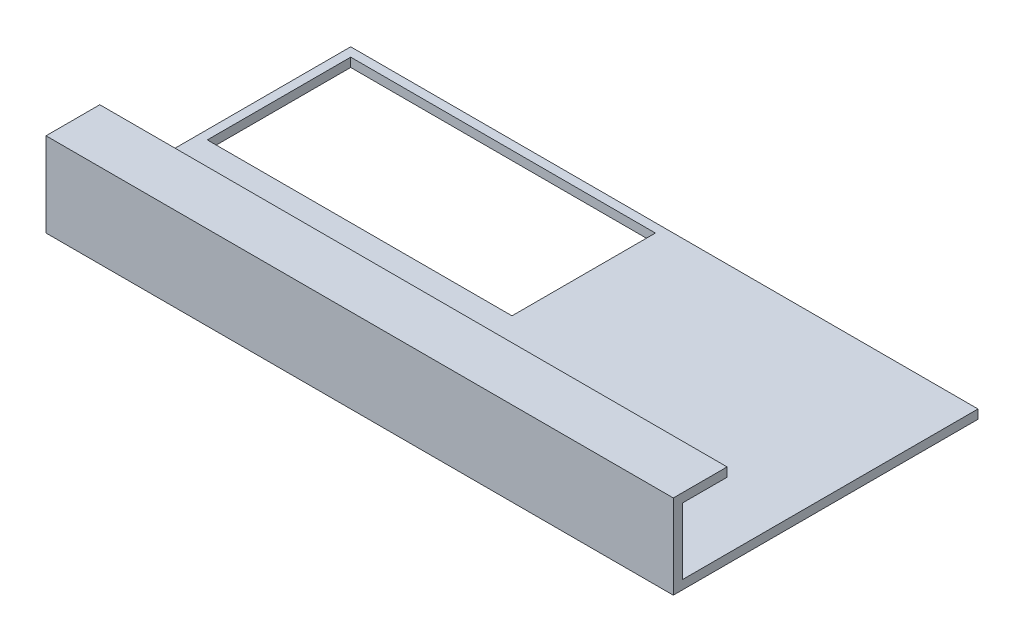
SolidWorks part; units mm, degrees
ref_plane "Front Plane" through (0, 0, 0) normal (0, 0, 1) x (1, 0, 0)
ref_plane "Top Plane" through (0, 0, 0) normal (0, 1, 0) x (1, 0, 0)
ref_plane "Right Plane" through (0, 0, 0) normal (1, 0, 0) x (0, 0, -1)
sketch "Sketch1" plane through (0, 0, 0) normal (0, 1, 0) x (1, 0, 0)
  line L1 (-87.5, -42.5) -> (87.5, -42.5)
  line L2 (-87.5, -42.5) -> (-87.5, 42.5)
  line L3 (-87.5, 42.5) -> (87.5, 42.5)
  line L4 (87.5, -42.5) -> (87.5, 42.5)
  line L5 (-87.5, -42.5) -> (87.5, 42.5) construction
  line L6 (-87.5, 42.5) -> (87.5, -42.5) construction
  point P0 (0, 0)
  dimension "D1" = 175
  dimension "D2" = 85
extrude "Boss-Extrude1" add sketch "Sketch1" along normal blind 2.5
sketch "Sketch2" plane through (0, 0, 0) normal (0, -1, 0) x (1, 0, 0)
  line L0 (-85, 0) -> (-85, -40)
  line L3 (-85, 0) -> (0, 0)
  line L4 (0, -40) -> (0, 0)
  line L5 (0, -40) -> (-85, -40)
  dimension "D1" = 85
  dimension "D2" = 40
extrude "Cut-Extrude1" cut sketch "Sketch2" against normal up to surface (2.5 mm away) up to face at (0, 2.5, 0)
sketch "Sketch3" plane through (0, 2.5, 0) normal (0, 1, 0) x (1, 0, 0)
  line L0 (87.5, -42.5) -> (87.5, 42.5) construction
  line L1 (-87.5, -42.5) -> (87.5, -42.5)
  line L2 (-87.5, -42.5) -> (-87.5, -40)
  line L3 (-87.5, -40) -> (87.5, -40)
  line L4 (87.5, -42.5) -> (87.5, -40)
  dimension "D1" = 2.5
extrude "Boss-Extrude2" add sketch "Sketch3" along normal blind 18.5
sketch "Sketch4" plane through (0, 21, 0) normal (0, 1, 0) x (1, 0, 0)
  line L0 (87.5, -40) -> (87.5, 42.5) construction
  line L1 (-87.5, -42.5) -> (87.5, -42.5)
  line L2 (-87.5, -42.5) -> (-87.5, -27.495)
  line L3 (-87.5, -27.495) -> (87.5, -27.495)
  line L4 (87.5, -42.5) -> (87.5, -27.495)
extrude "Boss-Extrude3" add sketch "Sketch4" along normal blind 2.5
